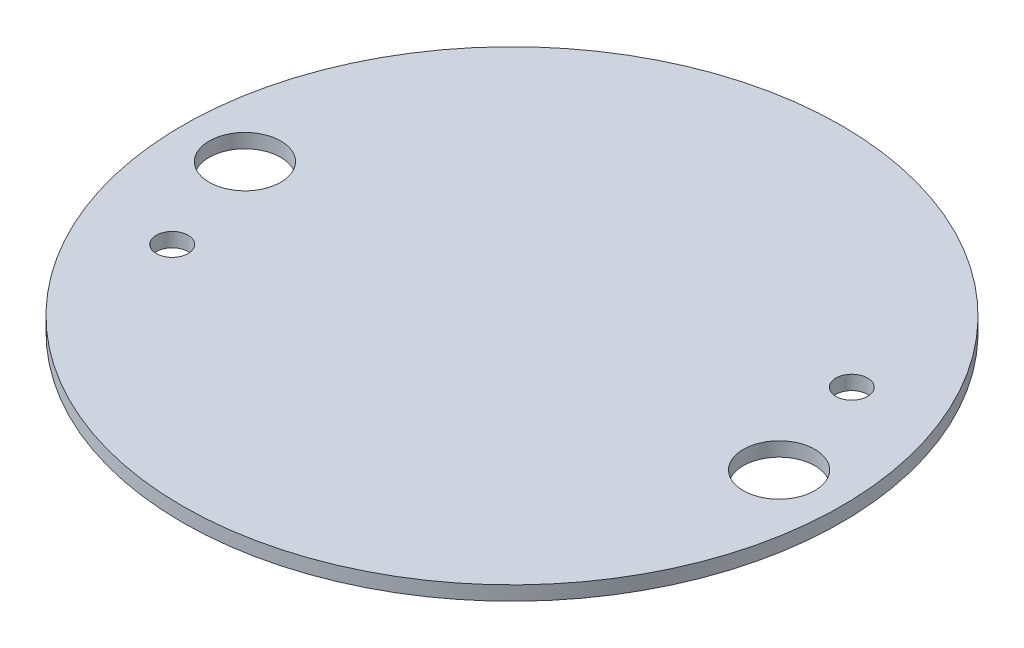
SolidWorks part; units mm, degrees
ref_plane "Front Plane" through (0, 0, 0) normal (0, 0, 1) x (1, 0, 0)
ref_plane "Top Plane" through (0, 0, 0) normal (0, 1, 0) x (1, 0, 0)
ref_plane "Right Plane" through (0, 0, 0) normal (1, 0, 0) x (0, 0, -1)
sketch "Sketch1" plane through (0, 0, 0) normal (0, 1, 0) x (1, 0, 0)
  circle A0 centre (0, 0) radius 73.66
extrude "Boss-Extrude1" add sketch "Sketch1" along normal blind 3.175
sketch "Sketch2" plane through (0, 3.175, 0) normal (0, 1, 0) x (1, 0, 0)
  line L0 (59.69, 0) -> (-59.69, 0) construction
  line L1 (-51.7955, -24.1526) -> (51.7955, 24.1526) construction
  circle A0 centre (-59.69, 0) radius 8.001
  circle A1 centre (59.69, 0) radius 8.001
  circle A2 centre (-51.7955, -24.1526) radius 3.556
  circle A3 centre (51.7955, 24.1526) radius 3.556
  point P5 (0, 0)
  point P11 (0, 0)
extrude "Cut-Extrude1" cut sketch "Sketch2" against normal blind 3.175
